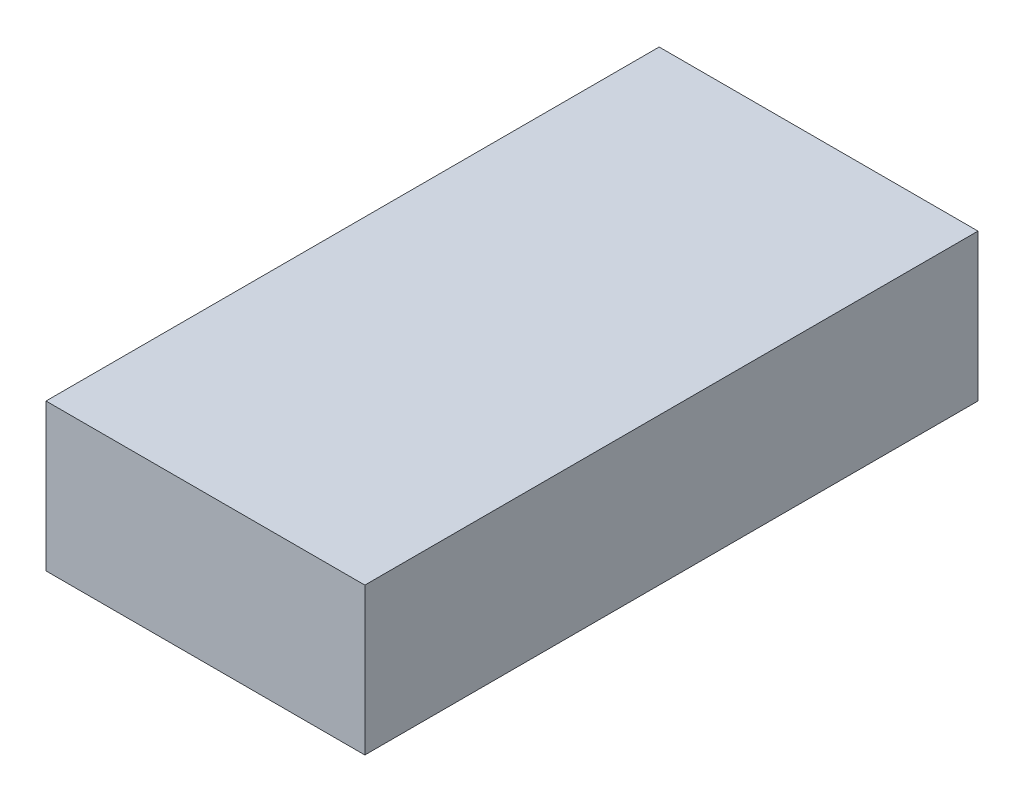
SolidWorks part; units mm, degrees
ref_plane "前视基准面" through (0, 0, 0) normal (0, 0, 1) x (1, 0, 0)
ref_plane "上视基准面" through (0, 0, 0) normal (0, 1, 0) x (1, 0, 0)
ref_plane "右视基准面" through (0, 0, 0) normal (1, 0, 0) x (0, 0, -1)
other "Configuration Table"
sketch "草图1" plane through (0, 0, 0) normal (0, 1, 0) x (1, 0, 0)
  line L5 (-13, -25) -> (13, -25)
  line L6 (-13, -25) -> (-13, 25)
  line L19 (-13, 25) -> (13, 25)
  line L20 (13, -25) -> (13, 25)
  line L29 (-13, -25) -> (13, 25) construction
  line L30 (-13, 25) -> (13, -25) construction
  point P0 (0, 0)
  dimension "D1" = 26
  dimension "D2" = 50
extrude "凸台-拉伸1" add sketch "草图1" along normal blind 12
